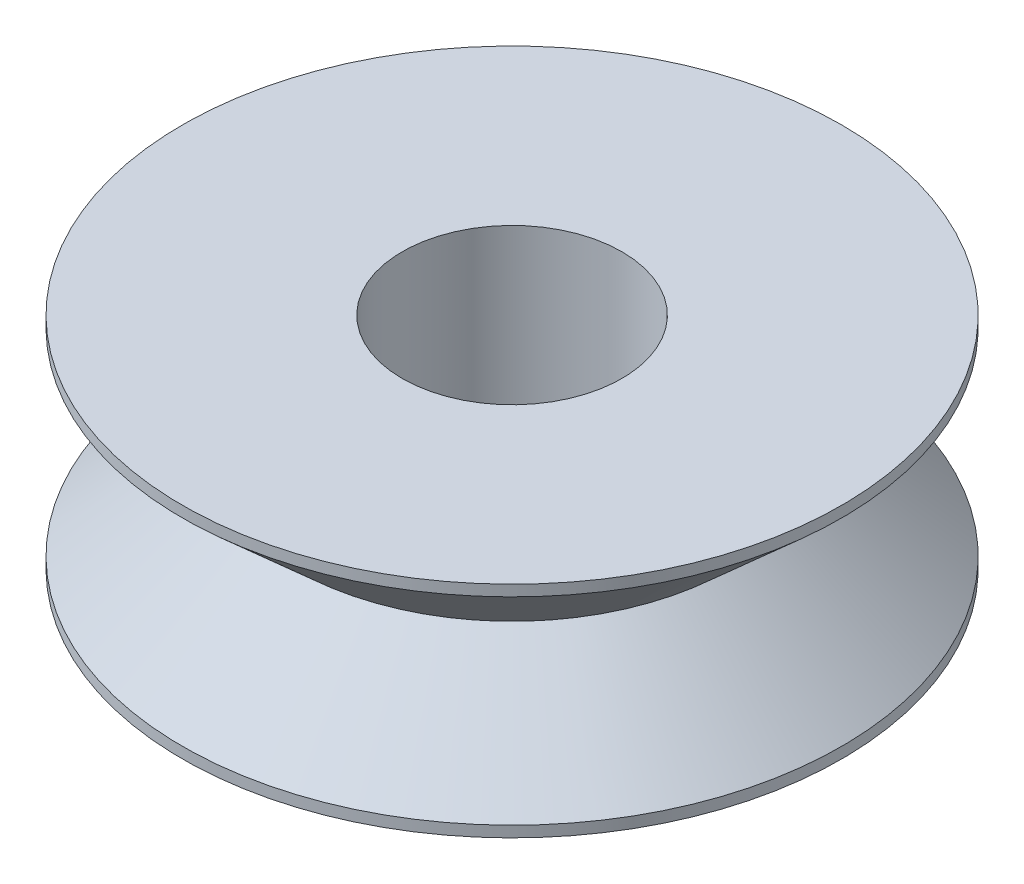
SolidWorks part; units mm, degrees
material "轴承钢"
ref_plane "前视基准面" through (0, 0, 0) normal (0, 0, 1) x (1, 0, 0)
ref_plane "上视基准面" through (0, 0, 0) normal (0, 1, 0) x (1, 0, 0)
ref_plane "右视基准面" through (0, 0, 0) normal (1, 0, 0) x (0, 0, -1)
sketch "草图1" plane through (0, 0, 0) normal (0, 0, 1) x (1, 0, 0)
  line L0 (2, 0) -> (6, 0)
  line L1 (0, 0) -> (0, 4) construction
  line L2 (2, 4) -> (6, 4)
  line L3 (6, 4) -> (6, 3.8)
  line L4 (6, 3.8) -> (4, 2)
  line L5 (4, 2) -> (6, 0.2)
  line L6 (6, 0.2) -> (6, 0)
  line L7 (0, 2) -> (4, 2) construction
  line L8 (2, 4) -> (2, 0)
  dimension "D1" = 4
  dimension "D2" = 6
  dimension "D3" = 2
  dimension "D5" = 0.2
  dimension "D6" = 2
revolve "旋转1" add sketch "草图1" angle 360 about L1
